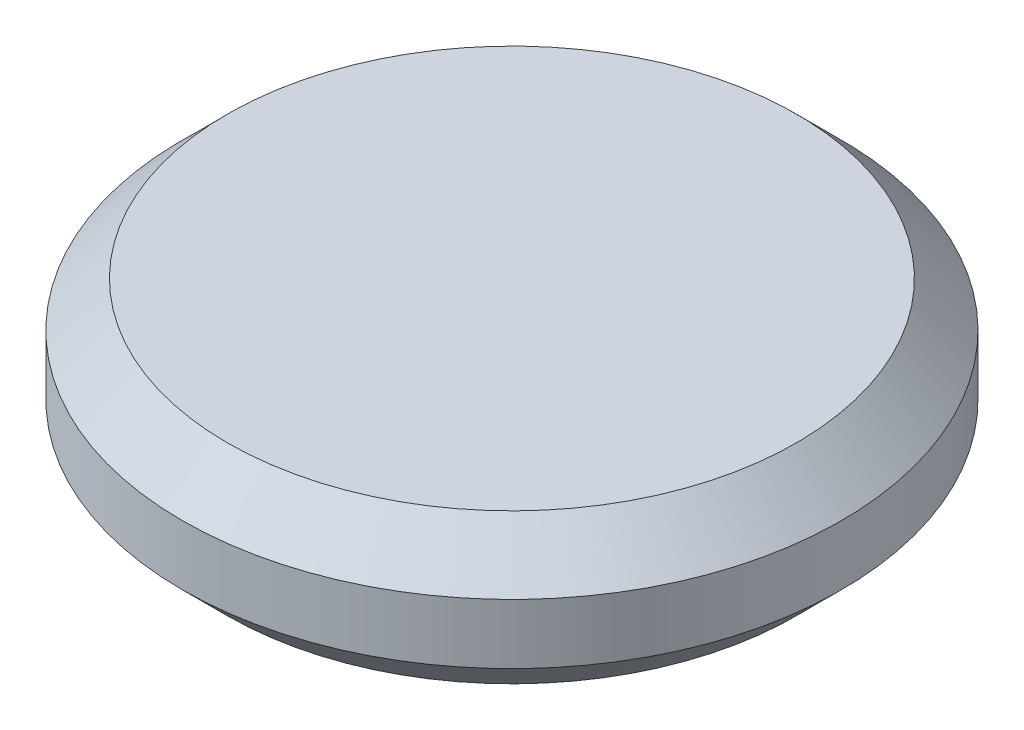
SolidWorks part; units mm, degrees
ref_plane "Front Plane" through (0, 0, 0) normal (0, 0, 1) x (1, 0, 0)
ref_plane "Top Plane" through (0, 0, 0) normal (0, 1, 0) x (1, 0, 0)
ref_plane "Right Plane" through (0, 0, 0) normal (1, 0, 0) x (0, 0, -1)
sketch "Sketch2" plane through (0, 0, 0) normal (0, 1, 0) x (1, 0, 0)
  circle A0 centre (0, 0) radius 110
extrude "Boss-Extrude1" add sketch "Sketch2" along normal blind 50
chamfer "Chamfer1" distance 15 2 edges at (0, 0, 110) (0, 50, 110)
scale "Scale1" scale about origin uniform scaling yes scale factor 0.333333
